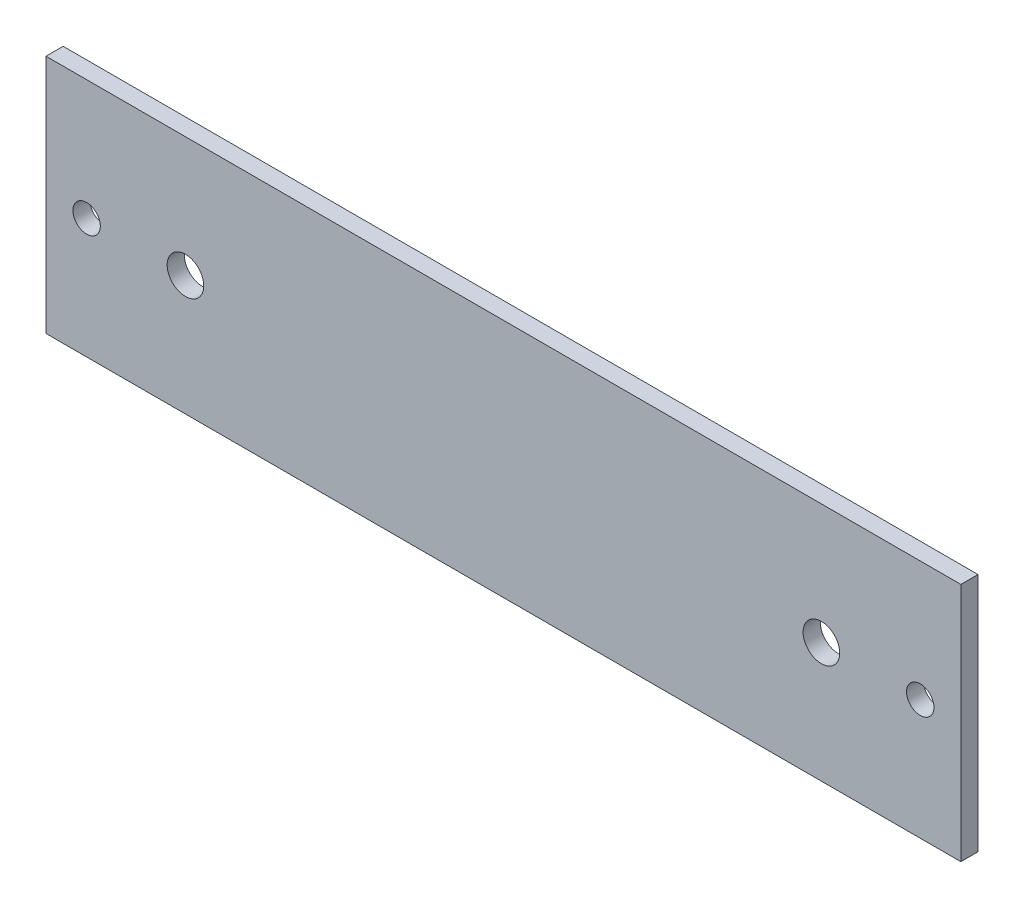
SolidWorks part; units mm, degrees
ref_plane "Front Plane" through (0, 0, 0) normal (0, 0, 1) x (1, 0, 0)
ref_plane "Top Plane" through (0, 0, 0) normal (0, 1, 0) x (1, 0, 0)
ref_plane "Right Plane" through (0, 0, 0) normal (1, 0, 0) x (0, 0, -1)
sketch "Sketch1" plane through (0, 0, 0) normal (0, 0, 1) x (1, 0, 0)
  line L0 (-40, 0) -> (40, 0) construction
  line L1 (-40, 10.5) -> (40, 10.5)
  line L2 (-40, 10.5) -> (-40, -10.5)
  line L3 (-40, -10.5) -> (40, -10.5)
  line L4 (40, 10.5) -> (40, -10.5)
  line L5 (-40, 10.5) -> (40, -10.5) construction
  line L6 (-40, -10.5) -> (40, 10.5) construction
  line L7 (0, 10.5) -> (0, -10.5) construction
  circle A0 centre (-36.45, 0) radius 1.2
  circle A1 centre (-27.805, 0) radius 1.6
  circle A2 centre (27.805, 0) radius 1.6
  circle A3 centre (36.45, 0) radius 1.2
  point P0 (0, 0)
  dimension "D3" = 3.2
  dimension "D4" = 2.4
  dimension "D1" = 21
  dimension "D2" = 80
  dimension "D5" = 72.9
  dimension "D6" = 55.61
extrude "Boss-Extrude1" add sketch "Sketch1" along normal blind 1.5
